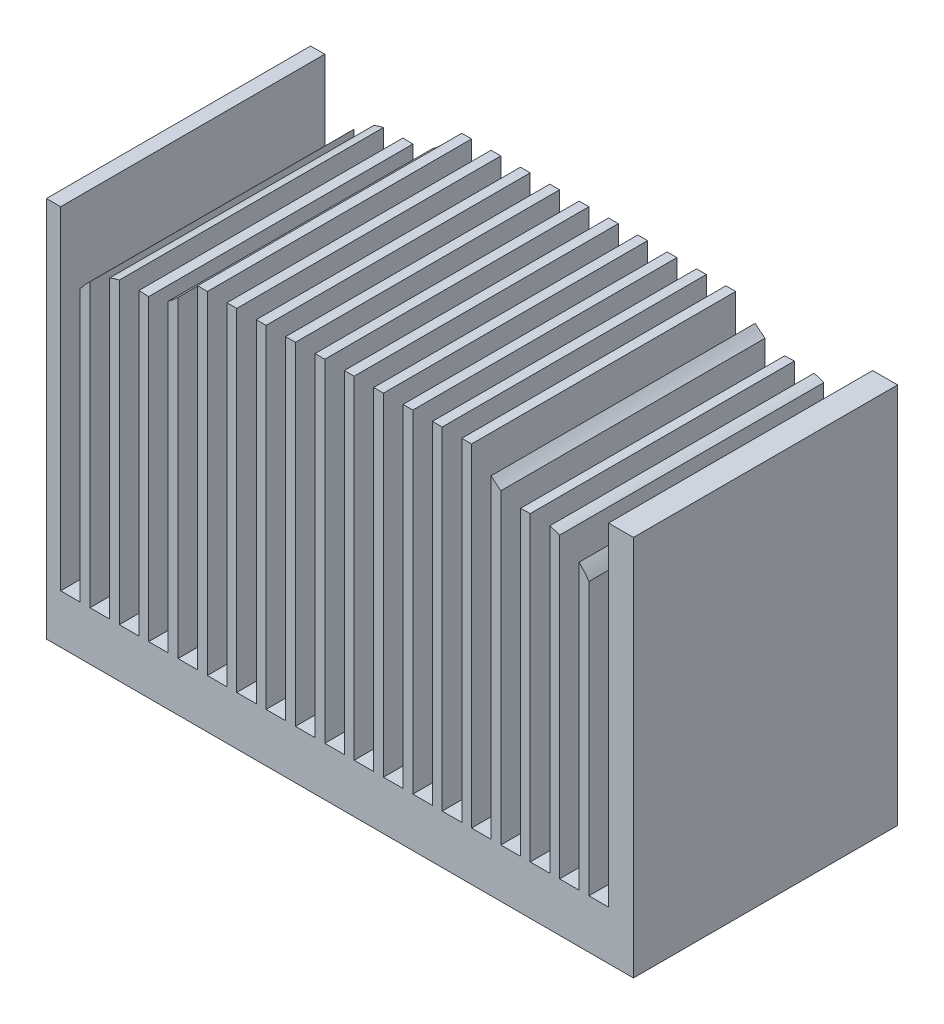
SolidWorks part; units mm, degrees
ref_plane "Front Plane" through (0, 0, 0) normal (0, 0, 1) x (1, 0, 0)
ref_plane "Top Plane" through (0, 0, 0) normal (0, 1, 0) x (1, 0, 0)
ref_plane "Right Plane" through (0, 0, 0) normal (1, 0, 0) x (0, 0, -1)
sketch "Sketch1" plane through (0, 0, 0) normal (0, 1, 0) x (1, 0, 0)
  line L1 (-30, 13.5) -> (30, 13.5)
  line L2 (-30, 13.5) -> (-30, -13.5)
  line L3 (-30, -13.5) -> (30, -13.5)
  line L4 (30, 13.5) -> (30, -13.5)
  line L5 (-30, 13.5) -> (30, -13.5) construction
  line L6 (-30, -13.5) -> (30, 13.5) construction
  point P0 (0, 0)
extrude "Boss-Extrude1" add sketch "Sketch1" along normal blind 39
sketch "Sketch2" plane through (0, 0, 13.5) normal (0, 0, 1) x (1, 0, 0)
  line L0 (-30, 39) -> (30, 39) construction
  line L1 (-28.5476, 39) -> (-26.5476, 39)
  line L2 (-28.5476, 39) -> (-28.5476, 5)
  line L3 (-28.5476, 5) -> (-26.5476, 5)
  line L4 (-26.5476, 39) -> (-26.5476, 5)
  line L5 (-30, 0) -> (30, 0) construction
  line L6 (-25.5476, 39) -> (-23.5476, 39)
  line L7 (-25.5476, 39) -> (-25.5476, 5)
  line L8 (-25.5476, 5) -> (-23.5476, 5)
  line L9 (-23.5476, 39) -> (-23.5476, 5)
  line L10 (-22.5476, 39) -> (-20.5476, 39)
  line L11 (-22.5476, 39) -> (-22.5476, 5)
  line L12 (-22.5476, 5) -> (-20.5476, 5)
  line L13 (-20.5476, 39) -> (-20.5476, 5)
  line L14 (-19.5476, 39) -> (-17.5476, 39)
  line L15 (-19.5476, 39) -> (-19.5476, 5)
  line L16 (-19.5476, 5) -> (-17.5476, 5)
  line L17 (-17.5476, 39) -> (-17.5476, 5)
  line L18 (-16.5476, 39) -> (-14.5476, 39)
  line L19 (-16.5476, 39) -> (-16.5476, 5)
  line L20 (-16.5476, 5) -> (-14.5476, 5)
  line L21 (-14.5476, 39) -> (-14.5476, 5)
  line L22 (-13.5476, 39) -> (-11.5476, 39)
  line L23 (-13.5476, 39) -> (-13.5476, 5)
  line L24 (-13.5476, 5) -> (-11.5476, 5)
  line L25 (-11.5476, 39) -> (-11.5476, 5)
  line L26 (-10.5476, 39) -> (-8.5476, 39)
  line L27 (-10.5476, 39) -> (-10.5476, 5)
  line L28 (-10.5476, 5) -> (-8.5476, 5)
  line L29 (-8.5476, 39) -> (-8.5476, 5)
  line L30 (-7.5476, 39) -> (-5.5476, 39)
  line L31 (-7.5476, 39) -> (-7.5476, 5)
  line L32 (-7.5476, 5) -> (-5.5476, 5)
  line L33 (-5.5476, 39) -> (-5.5476, 5)
  line L34 (-4.5476, 39) -> (-2.5476, 39)
  line L35 (-4.5476, 39) -> (-4.5476, 5)
  line L36 (-4.5476, 5) -> (-2.5476, 5)
  line L37 (-2.5476, 39) -> (-2.5476, 5)
  line L38 (-1.5476, 39) -> (0.4524, 39)
  line L39 (-1.5476, 39) -> (-1.5476, 5)
  line L40 (-1.5476, 5) -> (0.4524, 5)
  line L41 (0.4524, 39) -> (0.4524, 5)
  line L42 (1.4524, 39) -> (3.4524, 39)
  line L43 (1.4524, 39) -> (1.4524, 5)
  line L44 (1.4524, 5) -> (3.4524, 5)
  line L45 (3.4524, 39) -> (3.4524, 5)
  line L46 (4.4524, 39) -> (6.4524, 39)
  line L47 (4.4524, 39) -> (4.4524, 5)
  line L48 (4.4524, 5) -> (6.4524, 5)
  line L49 (6.4524, 39) -> (6.4524, 5)
  line L50 (7.4524, 39) -> (9.4524, 39)
  line L51 (7.4524, 39) -> (7.4524, 5)
  line L52 (7.4524, 5) -> (9.4524, 5)
  line L53 (9.4524, 39) -> (9.4524, 5)
  line L54 (10.4524, 39) -> (12.4524, 39)
  line L55 (10.4524, 39) -> (10.4524, 5)
  line L56 (10.4524, 5) -> (12.4524, 5)
  line L57 (12.4524, 39) -> (12.4524, 5)
  line L58 (13.4524, 39) -> (15.4524, 39)
  line L59 (13.4524, 39) -> (13.4524, 5)
  line L60 (13.4524, 5) -> (15.4524, 5)
  line L61 (15.4524, 39) -> (15.4524, 5)
  line L62 (16.4524, 39) -> (18.4524, 39)
  line L63 (16.4524, 39) -> (16.4524, 5)
  line L64 (16.4524, 5) -> (18.4524, 5)
  line L65 (18.4524, 39) -> (18.4524, 5)
  line L66 (19.4524, 39) -> (21.4524, 39)
  line L67 (19.4524, 39) -> (19.4524, 5)
  line L68 (19.4524, 5) -> (21.4524, 5)
  line L69 (21.4524, 39) -> (21.4524, 5)
  line L70 (22.4524, 39) -> (24.4524, 39)
  line L71 (22.4524, 39) -> (22.4524, 5)
  line L72 (22.4524, 5) -> (24.4524, 5)
  line L73 (24.4524, 39) -> (24.4524, 5)
  line L74 (25.4524, 39) -> (27.4524, 39)
  line L75 (25.4524, 39) -> (25.4524, 5)
  line L76 (25.4524, 5) -> (27.4524, 5)
  line L77 (27.4524, 39) -> (27.4524, 5)
  dimension "D1" = 5
  dimension "D2" = 19
extrude "Cut-Extrude1" cut sketch "Sketch2" against normal through all
sketch "Sketch3" plane through (0, 0, 13.5) normal (0, 0, 1) x (1, 0, 0)
  line L0 (0, 45.1218) -> (0, 53.2393) construction
  line L1 (-27.2873, 31.6397) -> (-27.2873, 46.9571)
  line L2 (-27.2873, 46.9571) -> (-15.8522, 46.9571)
  line L3 (-27.2873, 31.6397) -> (-40.0635, 31.6397) construction
  line L4 (-15.8522, 37.6396) -> (-15.8522, 46.9571)
  line L7 (14.7119, 37.8919) -> (14.7119, 46.9571)
  line L8 (26.147, 46.9571) -> (14.7119, 46.9571)
  line L9 (26.147, 31.6397) -> (26.147, 46.9571)
  spline S0 degree 3 poles (-27.2873, 31.6397) (-26.2006, 33.5588) (-23.3158, 36.3086) (-18.3267, 35.0927) (-16.8126, 36.7269) (-15.8522, 37.6396) knots 0 0 0 0 0.219185 0.330933 0.438558 0.438558 0.438558 0.438558
  spline S2 degree 3 poles (26.147, 31.6397) (25.0604, 33.8389) (22.1755, 36.5544) (17.1865, 35.3462) (15.6724, 36.9792) (14.7119, 37.8919) knots 0 0 0 0 0.219185 0.330933 0.438558 0.438558 0.438558 0.438558
extrude "Cut-Extrude3" cut sketch "Sketch3" against normal through all
sketch "Sketch4" plane through (0, 0, 0) normal (0, -1, 0) x (1, 0, 0)
  line L0 (0, 0) -> (0, 19.7084) construction
  circle A0 centre (-26.861, 0) radius 2
  circle A1 centre (26.861, 0) radius 2
extrude "Cut-Extrude4" cut sketch "Sketch4" against normal blind 8
